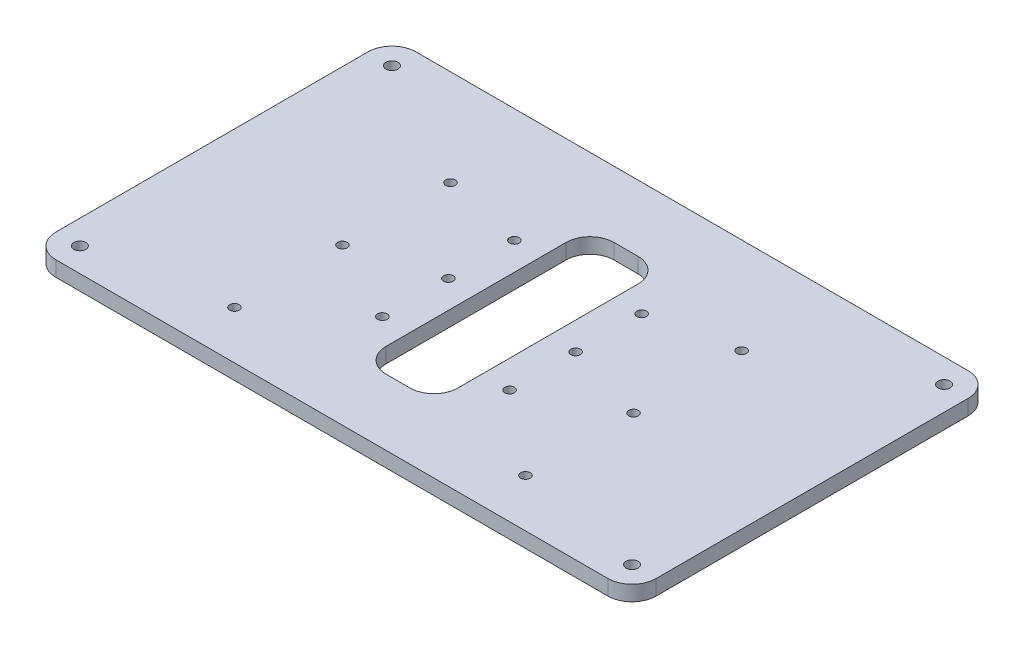
SolidWorks part; units mm, degrees
ref_plane "Front Plane" through (0, 0, 0) normal (0, 0, 1) x (1, 0, 0)
ref_plane "Top Plane" through (0, 0, 0) normal (0, 1, 0) x (1, 0, 0)
ref_plane "Right Plane" through (0, 0, 0) normal (1, 0, 0) x (0, 0, -1)
sketch "Sketch1" plane through (0, 0, 0) normal (0, 1, 0) x (1, 0, 0)
  line L0 (-125, 0) -> (125, 0) construction
  line L1 (-125, 75) -> (125, 75)
  line L2 (-125, 75) -> (-125, -75)
  line L3 (-125, -75) -> (125, -75)
  line L4 (125, 75) -> (125, -75)
  point P6 (0, 0)
  dimension "D1" = 150
  dimension "D2" = 250
extrude "Boss-Extrude1" add sketch "Sketch1" along normal blind 6.35
sketch "Sketch2" plane through (0, 6.35, 0) normal (0, 1, 0) x (1, 0, 0)
  line L0 (-15, 0) -> (15, 0) construction
  line L1 (-15, 47.5) -> (15, 47.5)
  line L2 (-15, 47.5) -> (-15, -47.5)
  line L3 (-15, -47.5) -> (15, -47.5)
  line L4 (15, 47.5) -> (15, -47.5)
  line L5 (-115, 65) -> (115, 65) construction
  line L6 (115, 65) -> (-115, -65) construction
  line L7 (-115, -65) -> (115, -65) construction
  line L8 (115, -65) -> (115, 65) construction
  line L9 (-115, 65) -> (-115, -65) construction
  line L10 (125, 75) -> (-125, 75) construction
  line L11 (-125, 75) -> (-125, -75) construction
  circle A0 centre (-115, 65) radius 2.5
  circle A1 centre (115, 65) radius 2.5
  circle A2 centre (115, -65) radius 2.5
  circle A3 centre (-115, -65) radius 2.5
  point P6 (0, 0)
  point P12 (0, 0)
  dimension "D4" = 5
  dimension "D1" = 30
  dimension "D2" = 95
  dimension "D3" = 10
  dimension "D5" = 10
extrude "Cut-Extrude1" cut sketch "Sketch2" against normal through all
fillet "Fillet1" radius 10 8 edges at (-125, 3.175, 75) (-125, 3.175, -75) (125, 3.175, -75) (125, 3.175, 75) (15, 3.175, -47.5) (-15, 3.175, -47.5) (15, 3.175, 47.5) (-15, 3.175, 47.5)
sketch "Sketch3" plane through (0, 6.35, 0) normal (0, 1, 0) x (1, 0, 0)
  line L0 (0, -75) -> (0, 75) construction
  line L1 (-115, -75) -> (115, -75) construction
  line L2 (115, 75) -> (-115, 75) construction
  line L3 (-60.62, -55) -> (60.62, -55) construction
  line L4 (-60.62, -10) -> (60.62, -10) construction
  line L5 (-60.62, -55) -> (-60.62, 35) construction
  line L6 (-60.62, 35) -> (60.62, 35) construction
  line L7 (60.62, 35) -> (60.62, -55) construction
  line L8 (-26.5, 27.5) -> (-26.5, -27.5) construction
  line L9 (-26.5, -27.5) -> (26.5, -27.5) construction
  line L10 (26.5, -27.5) -> (26.5, 27.5) construction
  line L11 (26.5, 27.5) -> (-26.5, 27.5) construction
  line L12 (-26.5, 0) -> (26.5, 0) construction
  circle A0 centre (-60.62, 35) radius 2
  circle A1 centre (-60.62, -10) radius 2
  circle A2 centre (-60.62, -55) radius 2
  circle A3 centre (60.62, 35) radius 2
  circle A4 centre (60.62, -10) radius 2
  circle A5 centre (60.62, -55) radius 2
  circle A6 centre (-26.5, 27.5) radius 2
  circle A8 centre (-26.5, -27.5) radius 2
  circle A9 centre (26.5, -27.5) radius 2
  circle A11 centre (26.5, 27.5) radius 2
  circle A12 centre (-26.5, 0) radius 2
  circle A13 centre (26.5, 0) radius 2
  point P8 (0, -55)
  point P24 (0, 27.5)
  dimension "D5" = 4
  dimension "D8" = 4
  dimension "D9" = 4
  dimension "D1" = 121.24
  dimension "D2" = 20
  dimension "D3" = 45
  dimension "D4" = 45
  dimension "D6" = 10
  dimension "D7" = 26.5
extrude "Cut-Extrude2" cut sketch "Sketch3" against normal through all
